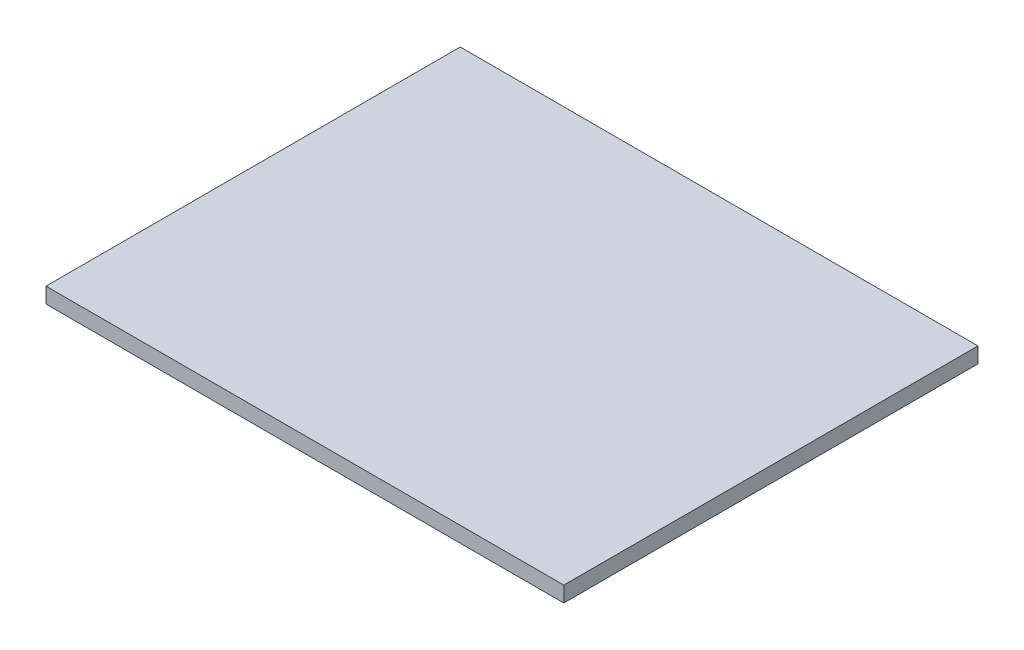
SolidWorks part; units mm, degrees
ref_plane "정면" through (0, 0, 0) normal (0, 0, 1) x (1, 0, 0)
ref_plane "윗면" through (0, 0, 0) normal (0, 1, 0) x (1, 0, 0)
ref_plane "우측면" through (0, 0, 0) normal (1, 0, 0) x (0, 0, -1)
sketch "스케치1" plane through (0, 0, 0) normal (0, 1, 0) x (1, 0, 0)
  line L1 (0, 0) -> (100, 0)
  line L2 (0, 0) -> (0, 80)
  line L3 (0, 80) -> (100, 80)
  line L4 (100, 0) -> (100, 80)
  dimension "D1" = 100
  dimension "D2" = 80
extrude "보스-돌출1" add sketch "스케치1" along normal blind 3
